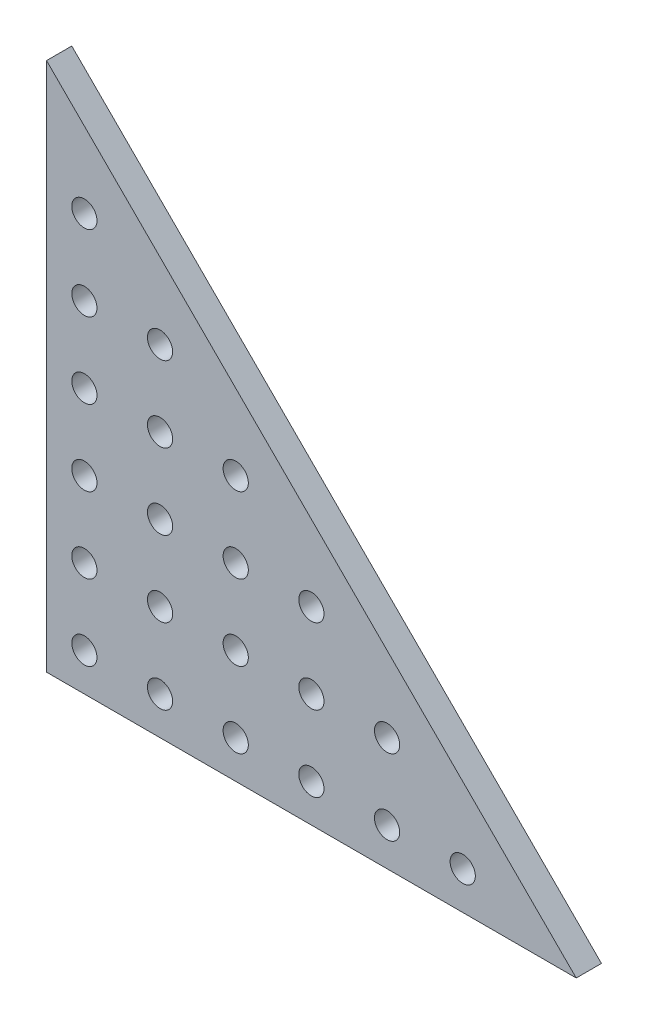
SolidWorks part; units mm, degrees
ref_plane "Alzado" through (0, 0, 0) normal (0, 0, 1) x (1, 0, 0)
ref_plane "Planta" through (0, 0, 0) normal (0, 1, 0) x (1, 0, 0)
ref_plane "Vista lateral" through (0, 0, 0) normal (1, 0, 0) x (0, 0, -1)
sketch "Model" plane through (0, 0, 0) normal (0, 0, 1) x (1, 0, 0)
  line L0 (-105.9434, 105.5565) -> (-105.9434, 42.5565)
  line L1 (-105.9434, 42.5565) -> (-42.9434, 42.5565)
  line L2 (-105.9434, 105.5565) -> (-42.9434, 42.5565)
  circle A0 centre (-101.4434, 92.0565) radius 1.5
  circle A1 centre (-101.4434, 83.0565) radius 1.5
  circle A2 centre (-92.4434, 83.0565) radius 1.5
  circle A3 centre (-101.4434, 74.0565) radius 1.5
  circle A4 centre (-92.4434, 74.0565) radius 1.5
  circle A5 centre (-83.4434, 74.0565) radius 1.5
  circle A6 centre (-101.4434, 65.0565) radius 1.5
  circle A7 centre (-92.4434, 65.0565) radius 1.5
  circle A8 centre (-83.4434, 65.0565) radius 1.5
  circle A9 centre (-74.4434, 65.0565) radius 1.5
  circle A10 centre (-101.4434, 56.0565) radius 1.5
  circle A11 centre (-92.4434, 56.0565) radius 1.5
  circle A12 centre (-83.4434, 56.0565) radius 1.5
  circle A13 centre (-74.4434, 56.0565) radius 1.5
  circle A14 centre (-65.4434, 56.0565) radius 1.5
  circle A15 centre (-101.4434, 47.0565) radius 1.5
  circle A16 centre (-92.4434, 47.0565) radius 1.5
  circle A17 centre (-83.4434, 47.0565) radius 1.5
  circle A18 centre (-74.4434, 47.0565) radius 1.5
  circle A19 centre (-65.4434, 47.0565) radius 1.5
  circle A20 centre (-56.4434, 47.0565) radius 1.5
extrude "Saliente-Extruir1" add sketch "Model" along normal blind 3
